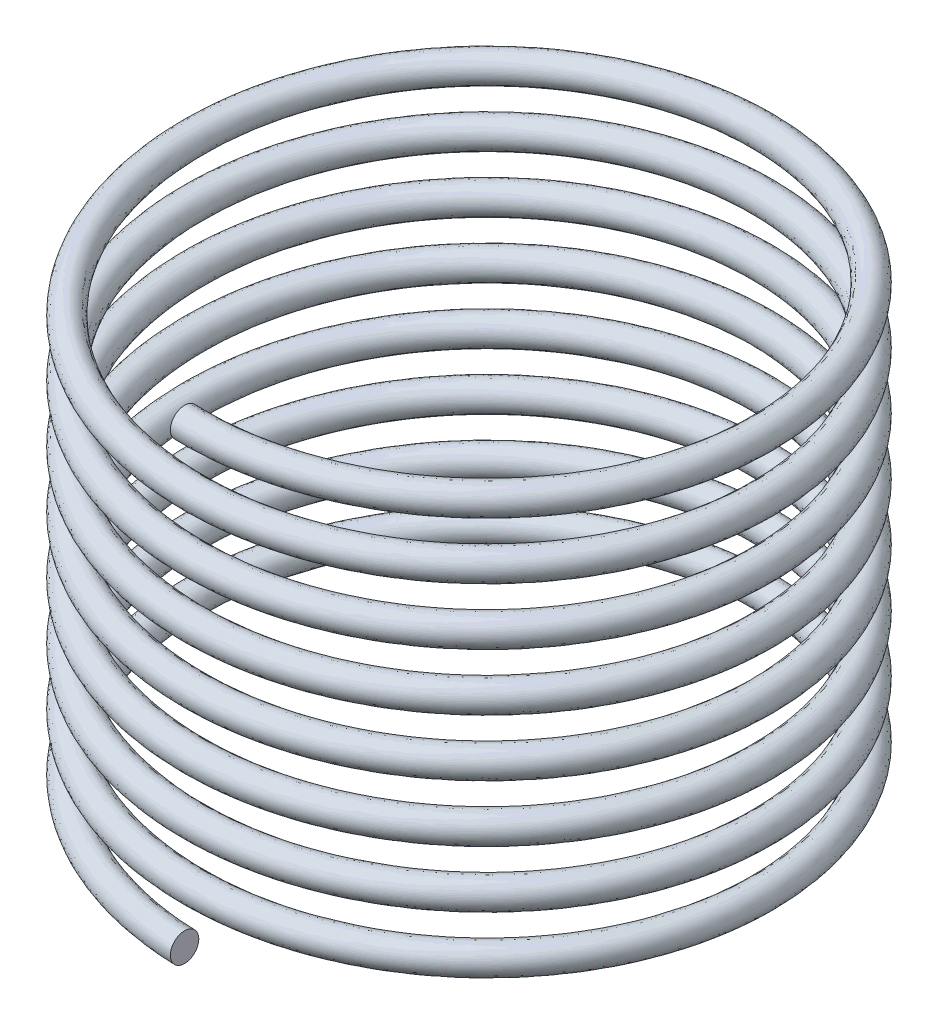
SolidWorks part; units mm, degrees
ref_plane "Front Plane" through (0, 0, 0) normal (0, 0, 1) x (1, 0, 0)
ref_plane "Top Plane" through (0, 0, 0) normal (0, 1, 0) x (1, 0, 0)
ref_plane "Right Plane" through (0, 0, 0) normal (1, 0, 0) x (0, 0, -1)
sketch "Sketch1" plane through (0, 0, 0) normal (0, 1, 0) x (1, 0, 0)
  circle A0 centre (0, 0) radius 50
  dimension "D1" = 100
curve "Helix/Spiral1" pitch 10 height 80 turns 8
sketch "Sketch3" plane through (0, 0, 0) normal (1, 0, 0) x (0, 0, -1)
  circle A0 centre (-50, 0) radius 2.5
  spline S0 degree 3 poles (-50, 0) (-50, 0.1065) (-49.324, 0.3201) (-46.3226, 0.64) (-41.455, 0.96) (-34.9171, 1.28) (-26.9725, 1.6) (-17.9411, 1.92) (-8.1868, 2.24) (1.8972, 2.56) (11.9049, 2.88) (21.4329, 3.2) (30.0974, 3.52) (37.5492, 3.84) (43.4882, 4.16) (47.6751, 4.48) (49.9411, 4.8) (50.195, 5.12) (48.4266, 5.44) (44.707, 5.76) (39.1863, 6.08) (32.0867, 6.4) (23.6943, 6.72) (14.3473, 7.04) (4.4223, 7.36) (-5.681, 7.68) (-15.5553, 8) (-24.8029, 8.32) (-33.0512, 8.64) (-39.9679, 8.96) (-45.2743, 9.28) (-48.7566, 9.6) (-50.2744, 9.92) (-49.7668, 10.24) (-47.254, 10.56) (-42.8374, 10.88) (-36.6948, 11.2) (-29.0739, 11.52) (-20.2815, 11.84) (-10.672, 12.16) (-0.6325, 12.48) (9.4324, 12.8) (19.1173, 13.12) (28.032, 13.44) (35.8173, 13.76) (42.1595, 14.08) (46.8031, 14.4) (49.561, 14.72) (50.3221, 15.04) (49.0558, 15.36) (45.8129, 15.68) (40.7243, 16) (33.9949, 16.32) (25.8959, 16.64) (16.7535, 16.96) (6.9361, 17.28) (-3.1608, 17.6) (-13.1302, 17.92) (-22.5707, 18.24) (-31.1018, 18.56) (-38.3798, 18.88) (-44.1115, 19.2) (-48.066, 19.52) (-50.0839, 19.84) (-50.0839, 20.16) (-48.066, 20.48) (-44.1115, 20.8) (-38.3798, 21.12) (-31.1018, 21.44) (-22.5707, 21.76) (-13.1302, 22.08) (-3.1608, 22.4) (6.9361, 22.72) (16.7535, 23.04) (25.8959, 23.36) (33.9949, 23.68) (40.7243, 24) (45.8129, 24.32) (49.0558, 24.64) (50.3221, 24.96) (49.561, 25.28) (46.8031, 25.6) (42.1595, 25.92) (35.8173, 26.24) (28.032, 26.56) (19.1173, 26.88) (9.4324, 27.2) (-0.6325, 27.52) (-10.672, 27.84) (-20.2815, 28.16) (-29.0739, 28.48) (-36.6948, 28.8) (-42.8374, 29.12) (-47.254, 29.44) (-49.7668, 29.76) (-50.2744, 30.08) (-48.7566, 30.4) (-45.2743, 30.72) (-39.9679, 31.04) (-33.0512, 31.36) (-24.8029, 31.68) (-15.5553, 32) (-5.681, 32.32) (4.4223, 32.64) (14.3473, 32.96) (23.6943, 33.28) (32.0867, 33.6) (39.1863, 33.92) (44.707, 34.24) (48.4266, 34.56) (50.195, 34.88) (49.9411, 35.2) (47.6751, 35.52) (43.4882, 35.84) (37.5492, 36.16) (30.0974, 36.48) (21.4329, 36.8) (11.9049, 37.12) (1.8972, 37.44) (-8.1868, 37.76) (-17.9411, 38.08) (-26.9725, 38.4) (-34.9171, 38.72) (-41.455, 39.04) (-46.3226, 39.36) (-49.324, 39.68) (-50.338, 40) (-49.324, 40.32) (-46.3226, 40.64) (-41.455, 40.96) (-34.9171, 41.28) (-26.9725, 41.6) (-17.9411, 41.92) (-8.1868, 42.24) (1.8972, 42.56) (11.9049, 42.88) (21.4329, 43.2) (30.0974, 43.52) (37.5492, 43.84) (43.4882, 44.16) (47.6751, 44.48) (49.9411, 44.8) (50.195, 45.12) (48.4266, 45.44) (44.707, 45.76) (39.1863, 46.08) (32.0867, 46.4) (23.6943, 46.72) (14.3473, 47.04) (4.4223, 47.36) (-5.681, 47.68) (-15.5553, 48) (-24.8029, 48.32) (-33.0512, 48.64) (-39.9679, 48.96) (-45.2743, 49.28) (-48.7566, 49.6) (-50.2744, 49.92) (-49.7668, 50.24) (-47.254, 50.56) (-42.8374, 50.88) (-36.6948, 51.2) (-29.0739, 51.52) (-20.2815, 51.84) (-10.672, 52.16) (-0.6325, 52.48) (9.4324, 52.8) (19.1173, 53.12) (28.032, 53.44) (35.8173, 53.76) (42.1595, 54.08) (46.8031, 54.4) (49.561, 54.72) (50.3221, 55.04) (49.0558, 55.36) (45.8129, 55.68) (40.7243, 56) (33.9949, 56.32) (25.8959, 56.64) (16.7535, 56.96) (6.9361, 57.28) (-3.1608, 57.6) (-13.1302, 57.92) (-22.5707, 58.24) (-31.1018, 58.56) (-38.3798, 58.88) (-44.1115, 59.2) (-48.066, 59.52) (-50.0839, 59.84) (-50.0839, 60.16) (-48.066, 60.48) (-44.1115, 60.8) (-38.3798, 61.12) (-31.1018, 61.44) (-22.5707, 61.76) (-13.1302, 62.08) (-3.1608, 62.4) (6.9361, 62.72) (16.7535, 63.04) (25.8959, 63.36) (33.9949, 63.68) (40.7243, 64) (45.8129, 64.32) (49.0558, 64.64) (50.3221, 64.96) (49.561, 65.28) (46.8031, 65.6) (42.1595, 65.92) (35.8173, 66.24) (28.032, 66.56) (19.1173, 66.88) (9.4324, 67.2) (-0.6325, 67.52) (-10.672, 67.84) (-20.2815, 68.16) (-29.0739, 68.48) (-36.6948, 68.8) (-42.8374, 69.12) (-47.254, 69.44) (-49.7668, 69.76) (-50.2744, 70.08) (-48.7566, 70.4) (-45.2743, 70.72) (-39.9679, 71.04) (-33.0512, 71.36) (-24.8029, 71.68) (-15.5553, 72) (-5.681, 72.32) (4.4223, 72.64) (14.3473, 72.96) (23.6943, 73.28) (32.0867, 73.6) (39.1863, 73.92) (44.707, 74.24) (48.4266, 74.56) (50.195, 74.88) (49.9411, 75.2) (47.6751, 75.52) (43.4882, 75.84) (37.5492, 76.16) (30.0974, 76.48) (21.4329, 76.8) (11.9049, 77.12) (1.8972, 77.44) (-8.1868, 77.76) (-17.9411, 78.08) (-26.9725, 78.4) (-34.9171, 78.72) (-41.455, 79.04) (-46.3226, 79.36) (-49.324, 79.6799) (-50, 79.8935) (-50, 80) knots 0 0 0 0 0.004 0.008 0.012 0.016 0.02 0.024 0.028 0.032 0.036 0.04 0.044 0.048 0.052 0.056 0.06 0.064 0.068 0.072 0.076 0.08 0.084 0.088 0.092 0.096 0.1 0.104 0.108 0.112 0.116 0.12 0.124 0.128 0.132 0.136 0.14 0.144 0.148 0.152 0.156 0.16 0.164 0.168 0.172 0.176 0.18 0.184 0.188 0.192 0.196 0.2 0.204 0.208 0.212 0.216 0.22 0.224 0.228 0.232 0.236 0.24 0.244 0.248 0.252 0.256 0.26 0.264 0.268 0.272 0.276 0.28 0.284 0.288 0.292 0.296 0.3 0.304 0.308 0.312 0.316 0.32 0.324 0.328 0.332 0.336 0.34 0.344 0.348 0.352 0.356 0.36 0.364 0.368 0.372 0.376 0.38 0.384 0.388 0.392 0.396 0.4 0.404 0.408 0.412 0.416 0.42 0.424 0.428 0.432 0.436 0.44 0.444 0.448 0.452 0.456 0.46 0.464 0.468 0.472 0.476 0.48 0.484 0.488 0.492 0.496 0.5 0.504 0.508 0.512 0.516 0.52 0.524 0.528 0.532 0.536 0.54 0.544 0.548 0.552 0.556 0.56 0.564 0.568 0.572 0.576 0.58 0.584 0.588 0.592 0.596 0.6 0.604 0.608 0.612 0.616 0.62 0.624 0.628 0.632 0.636 0.64 0.644 0.648 0.652 0.656 0.66 0.664 0.668 0.672 0.676 0.68 0.684 0.688 0.692 0.696 0.7 0.704 0.708 0.712 0.716 0.72 0.724 0.728 0.732 0.736 0.74 0.744 0.748 0.752 0.756 0.76 0.764 0.768 0.772 0.776 0.78 0.784 0.788 0.792 0.796 0.8 0.804 0.808 0.812 0.816 0.82 0.824 0.828 0.832 0.836 0.84 0.844 0.848 0.852 0.856 0.86 0.864 0.868 0.872 0.876 0.88 0.884 0.888 0.892 0.896 0.9 0.904 0.908 0.912 0.916 0.92 0.924 0.928 0.932 0.936 0.94 0.944 0.948 0.952 0.956 0.96 0.964 0.968 0.972 0.976 0.98 0.984 0.988 0.992 0.996 1 1 1 1 construction
  dimension "D1" = 5
sweep "Sweep1" add profiles "Sketch3" path "Helix/Spiral1"
